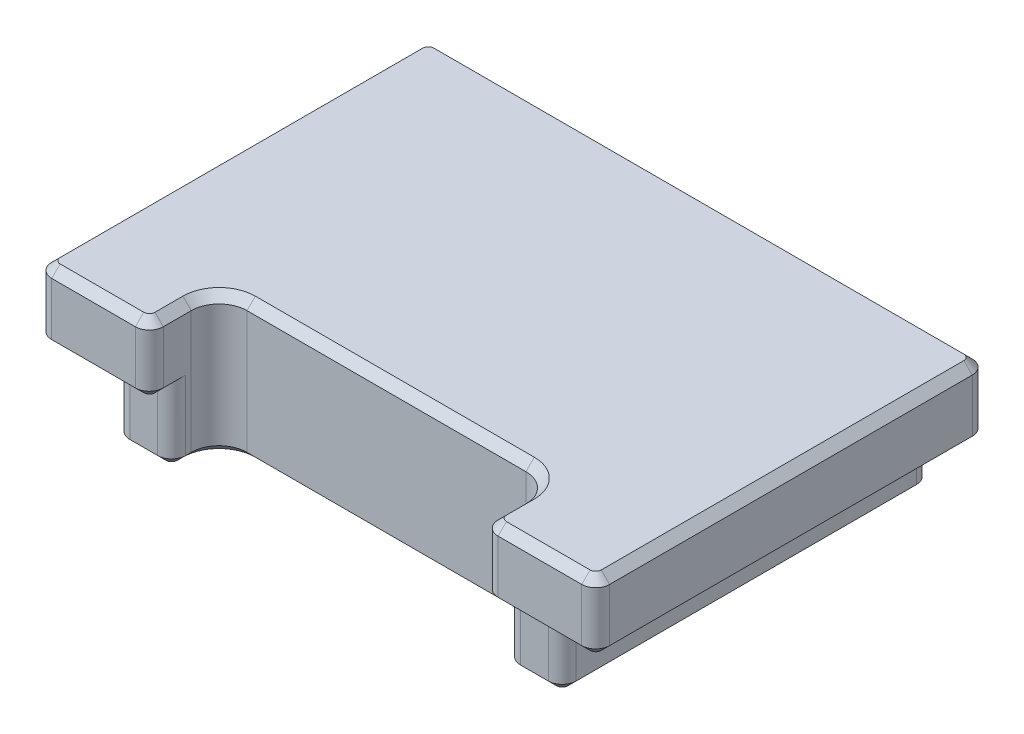
SolidWorks part; units mm, degrees
ref_plane "Front Plane" through (0, 0, 0) normal (0, 0, 1) x (1, 0, 0)
ref_plane "Top Plane" through (0, 0, 0) normal (0, 1, 0) x (1, 0, 0)
ref_plane "Right Plane" through (0, 0, 0) normal (1, 0, 0) x (0, 0, -1)
sketch "Sketch1" plane through (0, 0, 0) normal (0, 1, 0) x (1, 0, 0)
  line L1 (-20, -14) -> (20, -14)
  line L2 (-20, -14) -> (-20, 14)
  line L3 (-20, 14) -> (20, 14)
  line L4 (20, -14) -> (20, 14)
  line L5 (-20, -14) -> (20, 14) construction
  line L6 (-20, 14) -> (20, -14) construction
  point P0 (0, 0)
  dimension "D1" = 40
  dimension "D2" = 28
extrude "Boss-Extrude1" add sketch "Sketch1" along normal blind 10
sketch "Sketch2" plane through (0, 0, 0) normal (0, -1, 0) x (1, 0, 0)
  line L0 (20, 14) -> (20, -14) construction
  line L1 (-20, 14) -> (20, 14)
  line L2 (-20, 14) -> (-20, 12.4)
  line L3 (-20, 12.4) -> (20, 12.4)
  line L4 (20, 14) -> (20, 12.4)
  dimension "D1" = 1.6
extrude "Cut-Extrude1" cut sketch "Sketch2" against normal blind 5
sketch "Sketch3" plane through (0, 10, 0) normal (0, 1, 0) x (1, 0, 0)
  line L1 (-12, -19) -> (12, -19)
  line L2 (-12, -19) -> (-12, -9)
  line L3 (-12, -9) -> (12, -9)
  line L4 (12, -19) -> (12, -9)
  line L5 (-12, -19) -> (12, -9) construction
  line L6 (-12, -9) -> (12, -19) construction
  line L7 (-20, -14) -> (20, -14) construction
  point P0 (0, -14)
  dimension "D1" = 5
  dimension "D2" = 24
extrude "Cut-Extrude2" cut sketch "Sketch3" against normal through all contours L1 L4 L3 L2
sketch "Sketch4" plane through (0, 0, 0) normal (0, -1, 0) x (1, 0, 0)
  line L0 (20, -14) -> (-20, -14) construction
  line L1 (-20, 12.4) -> (-16, 12.4)
  line L2 (-20, 12.4) -> (-20, -14)
  line L3 (-20, -14) -> (-16, -14)
  line L4 (-16, 12.4) -> (-16, -14)
  line L6 (20, 12.4) -> (16, 12.4)
  line L7 (20, 12.4) -> (20, -14)
  line L8 (20, -14) -> (16, -14)
  line L9 (16, 12.4) -> (16, -14)
  dimension "D1" = 4
extrude "Cut-Extrude3" cut sketch "Sketch4" against normal up to surface (5 mm away) up to face at (16, 5, 13.2)
fillet "Fillet1" radius 2 2 edges at (12, 5, 9) (-12, 5, 9)
fillet "Fillet2" radius 1 12 edges at (16, 2.5, 12.4) (12, 2.5, 12.4) (-16, 2.5, 12.4) (-12, 2.5, 12.4) (20, 7.5, 14) (12, 7.5, 14) (-20, 7.5, 14) (-12, 7.5, 14) (-20, 7.5, -14) (-16, 2.5, -14) (20, 7.5, -14) (16, 2.5, -14)
chamfer "Chamfer2" distance 0.6 angle 45 46 edges at (12.2929, 10, 13.7071) (12, 10, 12) (11.4142, 10, 9.5858) (0, 10, 9) (-11.4142, 10, 9.5858) (-12, 10, 12) (-12.2929, 10, 13.7071) (-16, 10, 14) (-19.7071, 10, 13.7071) (-20, 10, 0) (0, 10, -14) (20, 10, 0) (19.7071, 10, 13.7071) (16, 10, 14) (19.7071, 10, -13.7071) (-19.7071, 10, -13.7071) (-15.7071, 0, 12.1071) (-14, 0, 12.4) (-12.2929, 0, 12.1071) (-12, 0, 11.2) (-11.4142, 0, 9.5858) (0, 0, 9) (11.4142, 0, 9.5858) (12, 0, 11.2) (12.2929, 0, 12.1071) (14, 0, 12.4) (15.7071, 0, 12.1071) (16, 0, -0.8) (15.7071, 0, -13.7071) (0, 0, -14) (-15.7071, 0, -13.7071) (-16, 0, -0.8) (-12, 5, 12.2) (-12.2929, 5, 13.7071) (-16, 5, 14) (-17, 5, -14) (-19.7071, 5, 13.7071) (-19.7071, 5, -13.7071) (-20, 5, 0) (12, 5, 12.2) (12.2929, 5, 13.7071) (17, 5, -14) (16, 5, 14) (19.7071, 5, -13.7071) (19.7071, 5, 13.7071) (20, 5, 0)
